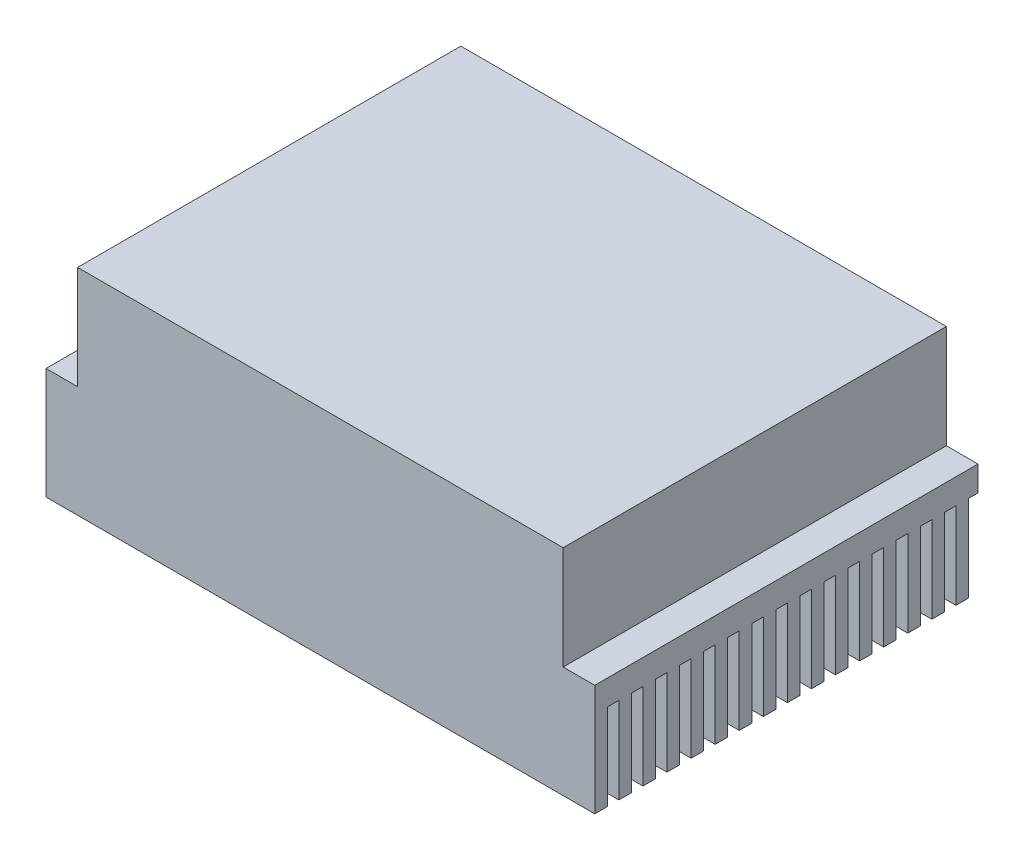
SolidWorks part; units mm, degrees
ref_plane "Front Plane" through (0, 0, 0) normal (0, 0, 1) x (1, 0, 0)
ref_plane "Top Plane" through (0, 0, 0) normal (0, 1, 0) x (1, 0, 0)
ref_plane "Right Plane" through (0, 0, 0) normal (1, 0, 0) x (0, 0, -1)
sketch "Sketch1" plane through (0, 0, 0) normal (0, 1, 0) x (1, 0, 0)
  line L1 (-61.468, 48.514) -> (61.468, 48.514)
  line L2 (-61.468, 48.514) -> (-61.468, -48.514)
  line L3 (-61.468, -48.514) -> (61.468, -48.514)
  line L4 (61.468, 48.514) -> (61.468, -48.514)
  line L5 (-61.468, 48.514) -> (61.468, -48.514) construction
  line L6 (-61.468, -48.514) -> (61.468, 48.514) construction
  point P0 (0, 0)
  dimension "D1" = 97.028
  dimension "D2" = 122.936
extrude "Boss-Extrude1" add sketch "Sketch1" along normal blind 26.162
sketch "Sketch2" plane through (0, 0, 0) normal (0, -1, 0) x (1, 0, 0)
  line L1 (-69.469, 48.514) -> (69.469, 48.514)
  line L2 (-69.469, 48.514) -> (-69.469, -48.514)
  line L3 (-69.469, -48.514) -> (69.469, -48.514)
  line L4 (69.469, 48.514) -> (69.469, -48.514)
  line L5 (-69.469, 48.514) -> (69.469, -48.514) construction
  line L6 (-69.469, -48.514) -> (69.469, 48.514) construction
  point P0 (0, 0)
  dimension "D1" = 97.028
  dimension "D2" = 138.938
extrude "Boss-Extrude2" add sketch "Sketch2" along normal blind 6.35
sketch "Sketch3" plane through (69.469, 0, 0) normal (1, 0, 0) x (0, 0, -1)
  line L0 (-42.418, -6.35) -> (-42.418, -28.194)
  line L1 (-48.514, -6.35) -> (-45.339, -6.35)
  line L2 (-48.514, -6.35) -> (-48.514, -28.194)
  line L3 (-48.514, -28.194) -> (-45.339, -28.194)
  line L4 (-45.339, -6.35) -> (-45.339, -28.194)
  line L5 (-42.418, -6.35) -> (-39.243, -6.35)
  line L6 (-39.243, -6.35) -> (-39.243, -28.194)
  line L7 (-42.418, -28.194) -> (-39.243, -28.194)
  line L8 (-36.322, -6.35) -> (-36.322, -28.194)
  line L9 (-36.322, -6.35) -> (-33.147, -6.35)
  line L10 (-33.147, -6.35) -> (-33.147, -28.194)
  line L11 (-36.322, -28.194) -> (-33.147, -28.194)
  line L12 (-30.226, -6.35) -> (-30.226, -28.194)
  line L13 (-30.226, -6.35) -> (-27.051, -6.35)
  line L14 (-27.051, -6.35) -> (-27.051, -28.194)
  line L15 (-30.226, -28.194) -> (-27.051, -28.194)
  line L16 (-24.13, -6.35) -> (-24.13, -28.194)
  line L17 (-24.13, -6.35) -> (-20.955, -6.35)
  line L18 (-20.955, -6.35) -> (-20.955, -28.194)
  line L19 (-24.13, -28.194) -> (-20.955, -28.194)
  line L20 (-18.034, -6.35) -> (-18.034, -28.194)
  line L21 (-18.034, -6.35) -> (-14.859, -6.35)
  line L22 (-14.859, -6.35) -> (-14.859, -28.194)
  line L23 (-18.034, -28.194) -> (-14.859, -28.194)
  line L24 (-11.938, -6.35) -> (-11.938, -28.194)
  line L25 (-11.938, -6.35) -> (-8.763, -6.35)
  line L26 (-8.763, -6.35) -> (-8.763, -28.194)
  line L27 (-11.938, -28.194) -> (-8.763, -28.194)
  line L28 (-5.842, -6.35) -> (-5.842, -28.194)
  line L29 (-5.842, -6.35) -> (-2.667, -6.35)
  line L30 (-2.667, -6.35) -> (-2.667, -28.194)
  line L31 (-5.842, -28.194) -> (-2.667, -28.194)
  line L32 (0.254, -6.35) -> (0.254, -28.194)
  line L33 (0.254, -6.35) -> (3.429, -6.35)
  line L34 (3.429, -6.35) -> (3.429, -28.194)
  line L35 (0.254, -28.194) -> (3.429, -28.194)
  line L36 (6.35, -6.35) -> (6.35, -28.194)
  line L37 (6.35, -6.35) -> (9.525, -6.35)
  line L38 (9.525, -6.35) -> (9.525, -28.194)
  line L39 (6.35, -28.194) -> (9.525, -28.194)
  line L40 (12.446, -6.35) -> (12.446, -28.194)
  line L41 (12.446, -6.35) -> (15.621, -6.35)
  line L42 (15.621, -6.35) -> (15.621, -28.194)
  line L43 (12.446, -28.194) -> (15.621, -28.194)
  line L44 (18.542, -6.35) -> (18.542, -28.194)
  line L45 (18.542, -6.35) -> (21.717, -6.35)
  line L46 (21.717, -6.35) -> (21.717, -28.194)
  line L47 (18.542, -28.194) -> (21.717, -28.194)
  line L48 (24.638, -6.35) -> (24.638, -28.194)
  line L49 (24.638, -6.35) -> (27.813, -6.35)
  line L50 (27.813, -6.35) -> (27.813, -28.194)
  line L51 (24.638, -28.194) -> (27.813, -28.194)
  line L52 (30.734, -6.35) -> (30.734, -28.194)
  line L53 (30.734, -6.35) -> (33.909, -6.35)
  line L54 (33.909, -6.35) -> (33.909, -28.194)
  line L55 (30.734, -28.194) -> (33.909, -28.194)
  line L56 (36.83, -6.35) -> (36.83, -28.194)
  line L57 (36.83, -6.35) -> (40.005, -6.35)
  line L58 (40.005, -6.35) -> (40.005, -28.194)
  line L59 (36.83, -28.194) -> (40.005, -28.194)
  line L60 (42.926, -6.35) -> (42.926, -28.194)
  line L61 (42.926, -6.35) -> (46.101, -6.35)
  line L62 (46.101, -6.35) -> (46.101, -28.194)
  line L63 (42.926, -28.194) -> (46.101, -28.194)
  dimension "D1" = 3.175
  dimension "D2" = 16
extrude "Boss-Extrude3" add sketch "Sketch3" along direction (-1, 0, 0) on the side against the normal through all
